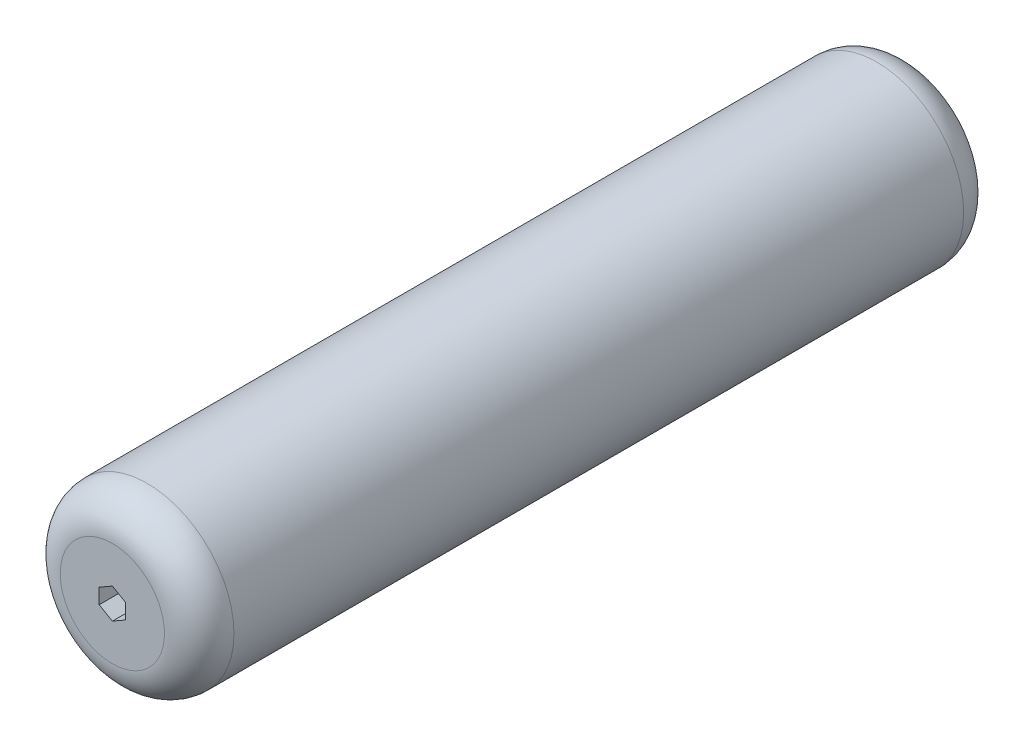
SolidWorks part; units mm, degrees
ref_plane "Front Plane" through (0, 0, 0) normal (0, 0, 1) x (1, 0, 0)
ref_plane "Top Plane" through (0, 0, 0) normal (0, 1, 0) x (1, 0, 0)
ref_plane "Right Plane" through (0, 0, 0) normal (1, 0, 0) x (0, 0, -1)
sketch "Sketch1" plane through (0, 0, 0) normal (0, 0, 1) x (1, 0, 0)
  line L1 (0, -5.5562) -> (4.8119, -2.7781)
  line L2 (4.8119, -2.7781) -> (4.8119, 2.7781)
  line L3 (4.8119, 2.7781) -> (0, 5.5563)
  line L4 (0, 5.5563) -> (-4.8119, 2.7781)
  line L5 (-4.8119, 2.7781) -> (-4.8119, -2.7781)
  line L6 (-4.8119, -2.7781) -> (0, -5.5562)
  circle A0 centre (0, 0) radius 4.8119 construction
  circle A1 centre (0, 0) radius 31.75
  dimension "D1" = 11.1125
extrude "Boss-Extrude1" add sketch "Sketch1" along normal blind 292.1
fillet "Fillet1" radius 12.7 1 edges at (31.75, 0, 292.1)
fillet "Fillet2" radius 12.7 1 edges at (31.75, 0, 0)
